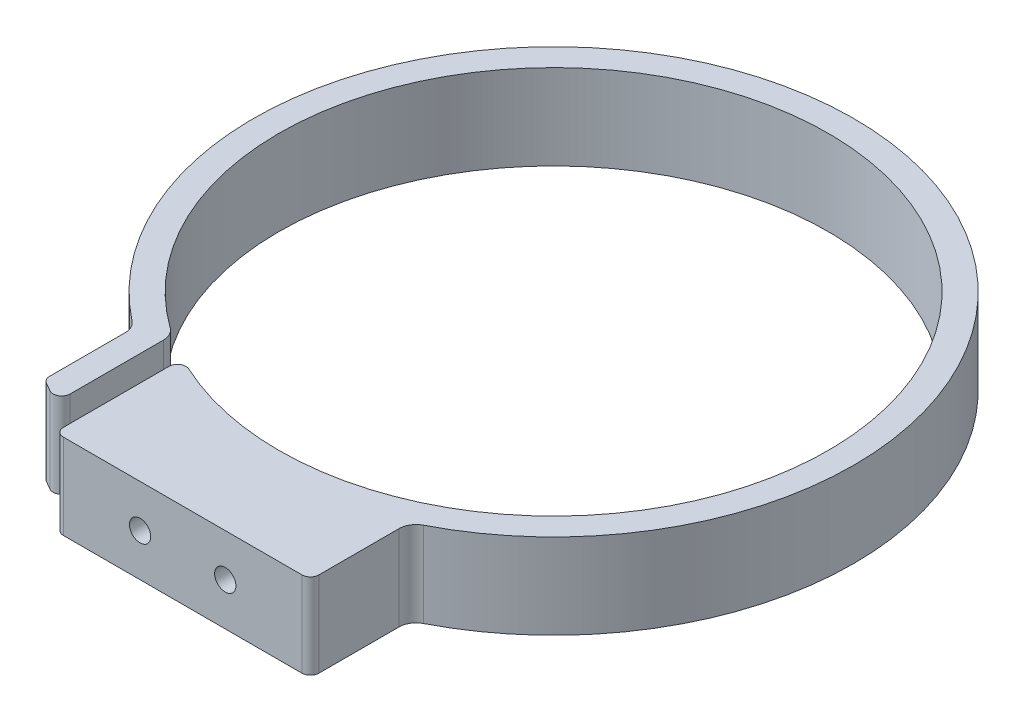
SolidWorks part; units mm, degrees
material "Сплав 2024"
ref_plane "Спереди" through (0, 0, 0) normal (0, 0, 1) x (1, 0, 0)
ref_plane "Сверху" through (0, 0, 0) normal (0, 1, 0) x (1, 0, 0)
ref_plane "Справа" through (0, 0, 0) normal (1, 0, 0) x (0, 0, -1)
sketch "Эскиз1" plane through (0, 0, 0) normal (0, 1, 0) x (1, 0, 0)
  line L0 (-15, -28.5493) -> (-15, -43.5493) construction
  line L1 (-15, -43.5493) -> (15, -43.5493) construction
  line L2 (15, -43.5493) -> (15, -28.5493) construction
  line L3 (15, -28.5493) -> (-15, -28.5493) construction
  line L4 (-15, -31.8993) -> (-15, -43.5493)
  line L5 (-15, -43.5493) -> (15, -43.5493)
  line L6 (15, -43.5493) -> (15, -31.8993)
  circle A0 centre (0, 0) radius 32.25
  arc A1 (15, -31.8993) -> (-15, -31.8993) centre (0, 0) ccw
  circle A3 centre (0, 0) radius 35.25 construction
  point P7 (-15, -31.8993)
  point P10 (15, -31.8993)
  point P12 (35.25, 0)
  dimension "D1" = 64.5
  dimension "D3" = 30
  dimension "D4" = 15
  dimension "D2" = 3
extrude "Бобышка-Вытянуть1" add sketch "Эскиз1" along normal blind 10
ref_plane "Плоскость1" through (15, 0, 0) normal (1, 0, 0) x (0, 0, -1)
ref_plane "Плоскость2" through (-15, 0, 0) normal (1, 0, 0) x (0, 0, -1)
sketch "Эскиз4" plane through (0, 10, 0) normal (0, 1, 0) x (1, 0, 0)
  line L1 (-15, -31.8993) -> (-18, -31.8993)
  line L2 (-15, -31.8993) -> (-15, -23.7125)
  line L3 (-15, -23.7125) -> (-18, -23.7125)
  line L4 (-18, -31.8993) -> (-18, -23.7125)
  dimension "D1" = 3
  dimension "D2" = 8.1867
extrude "Вырез-Вытянуть2" cut sketch "Эскиз4" against normal up to surface (10 mm away) up to face at (0, 0, 20.937)
sketch "Эскиз11" plane through (0, 10, 0) normal (0, 1, 0) x (1, 0, 0)
  line L1 (-18, -26.7593) -> (-21, -26.7593)
  line L2 (-18, -26.7593) -> (-18, -40.4914)
  line L3 (-18, -40.4914) -> (-21, -38.7593)
  line L4 (-21, -26.7593) -> (-21, -38.7593)
  dimension "D1" = 3
  dimension "D2" = 120
  dimension "D3" = 12
extrude "Бобышка-Вытянуть5" add sketch "Эскиз11" against normal up to surface (10 mm away) up to face at (0.037, 0, 13.8254)
sketch "Эскиз12" plane through (-21, 0, 0) normal (-1, 0, 0) x (0, 0, 1)
  line L0 (38.7593, 5) -> (28.3119, 5) construction
  line L1 (38.7593, 0) -> (38.7593, 10) construction
  line L2 (28.3119, 0) -> (28.3119, 10) construction
  line L3 (33.7593, 10) -> (33.7593, 0) construction
  dimension "D1" = 5
hole_wizard "Отверстие с зазором M32" positions "Эскиз14" profile "Эскиз13" hole size "M3" standard "Ansi Metric"
sketch "Эскиз14" plane through (-21, 0, 0) normal (-1, 0, 0) x (0, 0, 1)
  line L1 (33.7593, 10) -> (33.7593, 0) construction
  point P0 (33.7593, 5)
sketch "Эскиз13" plane through (-21, 5, 33.7593) normal (0, 1, 0) x (0, 0, 1)
  line L0 (0, 0) -> (0, 3)
  line L1 (0, 3) -> (1.7, 3)
  line L2 (1.7, 3) -> (1.7, 0)
  line L5 (1.7, 0) -> (0, 0)
  line L11 (0, -6.35) -> (0, 107.95) construction
  dimension "Диаметр сквозного отверстия" = 3.4
  dimension "Глубина сквозного отверстия" = 3
hole_wizard "Отверстие обработанное метчиком M3x0.51" positions "Эскиз16" profile "Эскиз15" tap size "M3x0.5" standard "Ansi Metric"
sketch "Эскиз16" plane through (-15, 0, 0) normal (-1, 0, 0) x (0, 0, 1)
  line L1 (33.7593, 10) -> (33.7593, 0) construction
  line L2 (38.7593, 5) -> (28.3119, 5) construction
  point P0 (33.7593, 5)
sketch "Эскиз15" plane through (-15, 5, 33.7593) normal (0, 1, 0) x (0, 0, 1)
  line L0 (0, 0) -> (0, 9.2511)
  line L1 (0, 9.2511) -> (1.25, 8.5)
  line L2 (1.25, 8.5) -> (1.25, 0)
  line L5 (1.25, 0) -> (0, 0)
  line L10 (0, 9.2511) -> (-1.25, 8.5) construction
  line L11 (0, -6.35) -> (0, 107.95) construction
  dimension "Диаметр сверла" = 2.5
  dimension "Глубина сверла" = 8.5
  dimension "Угол заточки сверла" = 118
cosmetic thread "Отверстие резьбы1" parameters "D1"=6, "D2"=3
sketch "Эскиз17" plane through (0, 0, 43.5493) normal (0, 0, 1) x (1, 0, 0)
  line L0 (-15, 5) -> (15, 5) construction
  line L1 (-15, 10) -> (-15, 0) construction
  line L2 (15, 10) -> (15, 0) construction
  line L3 (-5, 10) -> (-5, 0) construction
  line L4 (-15, 10) -> (15, 10) construction
  line L5 (-15, 0) -> (15, 0) construction
  line L6 (5, 10) -> (5, 0) construction
  line L7 (-15, 10) -> (-15, 0) construction
  dimension "D1" = 10
  dimension "D2" = 30
  dimension "D3" = 10
hole_wizard "Отверстие обработанное метчиком M3x0.52" positions "Эскиз19" profile "Эскиз18" tap size "M3x0.5" standard "Ansi Metric"
sketch "Эскиз19" plane through (0, 0, 43.5493) normal (0, 0, 1) x (1, 0, 0)
  line L0 (-5, 10) -> (-5, 0) construction
  line L1 (5, 10) -> (5, 0) construction
  point P0 (-5, 5)
  point P4 (5, 5)
sketch "Эскиз18" plane through (-5, 5, 43.5493) normal (1, 0, 0) x (0, -1, 0)
  line L0 (0, 0) -> (0, 9.2511)
  line L1 (0, 9.2511) -> (1.25, 8.5)
  line L2 (1.25, 8.5) -> (1.25, 0)
  line L5 (1.25, 0) -> (0, 0)
  line L10 (0, 9.2511) -> (-1.25, 8.5) construction
  line L11 (0, -6.35) -> (0, 107.95) construction
  dimension "Диаметр сверла" = 2.5
  dimension "Глубина сверла" = 8.5
  dimension "Угол заточки сверла" = 118
cosmetic thread "Отверстие резьбы2" parameters "D1"=6, "D2"=3
cosmetic thread "Отверстие резьбы3" parameters "D1"=6, "D2"=3
fillet "Скругление1" radius 2 3 edges at (15, 5, 31.8993) (-18, 5, 26.7593) (-21, 5, 28.3119)
fillet "Скругление2" radius 1 5 edges at (-15, 5, 28.5493) (-18, 5, 40.4914) (-21, 5, 38.7593) (15, 5, 43.5493) (-15, 5, 43.5493)
equation "\"D1@Эскиз17\"=\"D2@Эскиз17\"/3"
equation "\"D3@Эскиз17\"=\"D1@Эскиз17\""
